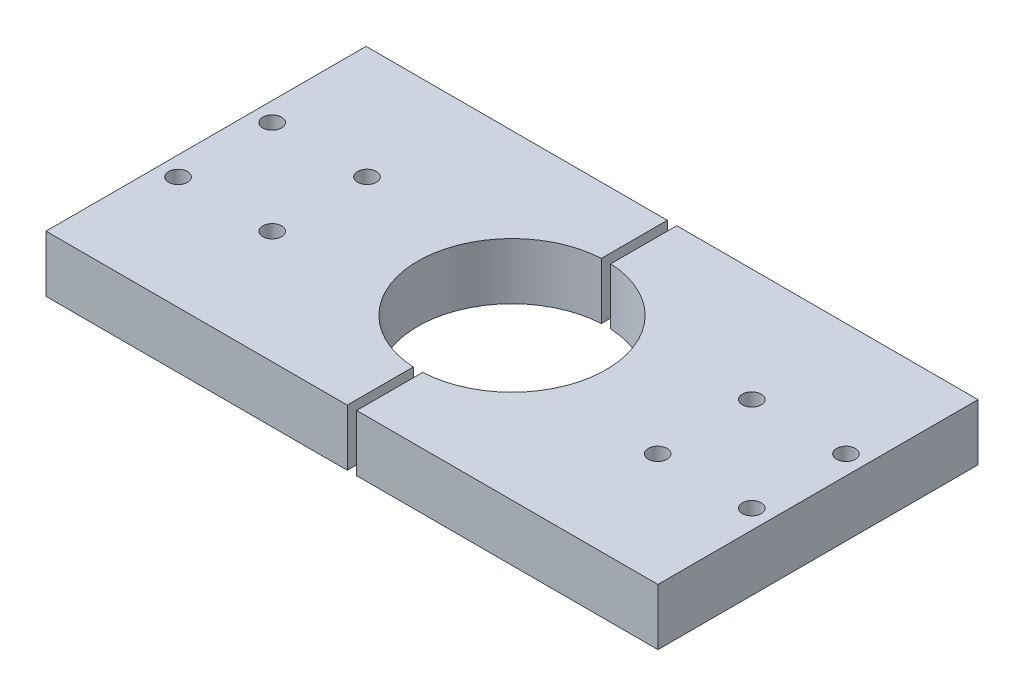
SolidWorks part; units mm, degrees
material "1060 Alloy"
ref_plane "Front Plane" through (0, 0, 0) normal (0, 0, 1) x (1, 0, 0)
ref_plane "Top Plane" through (0, 0, 0) normal (0, 1, 0) x (1, 0, 0)
ref_plane "Right Plane" through (0, 0, 0) normal (1, 0, 0) x (0, 0, -1)
sketch "Sketch1" plane through (0, 0, 0) normal (0, 1, 0) x (1, 0, 0)
  line L0 (1, 34) -> (65, 34)
  line L1 (-65, -34) -> (-1, -34)
  line L2 (-65, -34) -> (-65, 34)
  line L3 (-65, 34) -> (-1, 34)
  line L4 (65, -34) -> (65, 34)
  line L5 (-65, -34) -> (65, 34) construction
  line L6 (-65, 34) -> (65, -34) construction
  line L8 (-1, -34) -> (-1, 34)
  line L10 (1, -34) -> (1, 34)
  line L11 (-1, -34) -> (1, 34) construction
  line L12 (-1, 34) -> (1, -34) construction
  line L13 (1, -34) -> (65, -34)
  point P0 (0, 0)
  point P6 (0, 0)
  dimension "D1" = 68
  dimension "D2" = 130
  dimension "D3" = 2
extrude "Boss-Extrude1" add sketch "Sketch1" along normal blind 12
sketch "Sketch2" plane through (0, 0, 0) normal (0, 1, 0) x (1, 0, 0)
  circle A0 centre (0, 0) radius 20
  dimension "D1" = 40
extrude "Cut-Extrude1" cut sketch "Sketch2" along normal through all
sketch "Sketch3" plane through (0, 12, 0) normal (0, 1, 0) x (1, 0, 0)
  line L0 (-6.6, 0) -> (6.6, 0) construction
  line L1 (-60.95, -10) -> (-40.95, -10) construction
  line L2 (-60.95, -10) -> (-60.95, 10) construction
  line L3 (-60.95, 10) -> (-40.95, 10) construction
  line L4 (-40.95, -10) -> (-40.95, 10) construction
  line L5 (-60.95, -10) -> (-40.95, 10) construction
  line L6 (-60.95, 10) -> (-40.95, -10) construction
  line L7 (-65, 34) -> (-65, -34) construction
  circle A0 centre (-60.95, 10) radius 2
  circle A1 centre (-40.8892, 10.0829) radius 2
  circle A2 centre (-40.95, -10) radius 2
  circle A3 centre (-60.95, -10) radius 2
  point P0 (-50.95, 0)
  dimension "D3" = 4
  dimension "D1" = 20
  dimension "D2" = 4.05
  dimension "20" = 20
extrude "Cut-Extrude2" cut sketch "Sketch3" against normal through all
sketch "Sketch5" plane through (0, 12, 0) normal (0, 1, 0) x (1, 0, 0)
  line L0 (-6.6, 0) -> (6.6, 0) construction
  line L1 (40.95, -10) -> (60.95, -10) construction
  line L2 (40.95, -10) -> (40.95, 10) construction
  line L3 (40.95, 10) -> (60.95, 10) construction
  line L4 (60.95, -10) -> (60.95, 10) construction
  line L5 (40.95, -10) -> (60.95, 10) construction
  line L6 (40.95, 10) -> (60.95, -10) construction
  line L7 (65, -34) -> (65, 34) construction
  circle A0 centre (40.95, 10) radius 2
  circle A1 centre (60.95, 10) radius 2
  circle A2 centre (60.95, -10) radius 2
  circle A3 centre (40.95, -10) radius 2
  point P0 (50.95, 0)
  dimension "D4" = 4
  dimension "D1" = 20
  dimension "D2" = 20
  dimension "D3" = 4.05
  dimension "D5" = 2
  dimension "D6" = 2
extrude "Cut-Extrude3" cut sketch "Sketch5" against normal through all
sketch "Sketch6" plane through (-65, 0, 0) normal (-1, 0, 0) x (0, 0, 1)
  line L0 (-34, 12) -> (-34, 0) construction
  line L1 (-34, 12) -> (34, 12) construction
  line L2 (0, -6.6) -> (0, 6.6) construction
  circle A0 centre (-27, 6) radius 3
  circle A1 centre (27, 6) radius 3
  dimension "D1" = 6
  dimension "D2" = 7
  dimension "D3" = 6
extrude "Cut-Extrude4" cut sketch "Sketch6" against normal up to next (64 mm away)
sketch "Sketch7" plane through (-65, 0, 0) normal (-1, 0, 0) x (0, 0, 1)
  circle A0 centre (-27, 6) radius 5
  circle A1 centre (27, 6) radius 5
  dimension "D1" = 10
extrude "Cut-Extrude5" cut sketch "Sketch7" against normal blind 6
sketch "Sketch8" plane through (1, 0, 0) normal (-1, 0, 0) x (0, 0, 1)
  line L0 (0, -6.6) -> (0, 6.6) construction
  circle A0 centre (-27, 6) radius 2.5
  circle A1 centre (27, 6) radius 2.5
  dimension "D1" = 5
extrude "Cut-Extrude6" cut sketch "Sketch8" against normal blind 25
sketch "Sketch9" plane through (0, 0, 0) normal (0, 1, 0) x (1, 0, 0)
  line L0 (-1, 34) -> (-65, 34) construction
  line L1 (-65, -34) -> (-1, -34)
  line L2 (-65, -34) -> (-65, 34)
  line L3 (-65, 34) -> (-1, 34)
  line L4 (-1, -34) -> (-1, 34)
extrude "Cut-Extrude7" [suppressed] cut sketch "Sketch9" along normal through all
